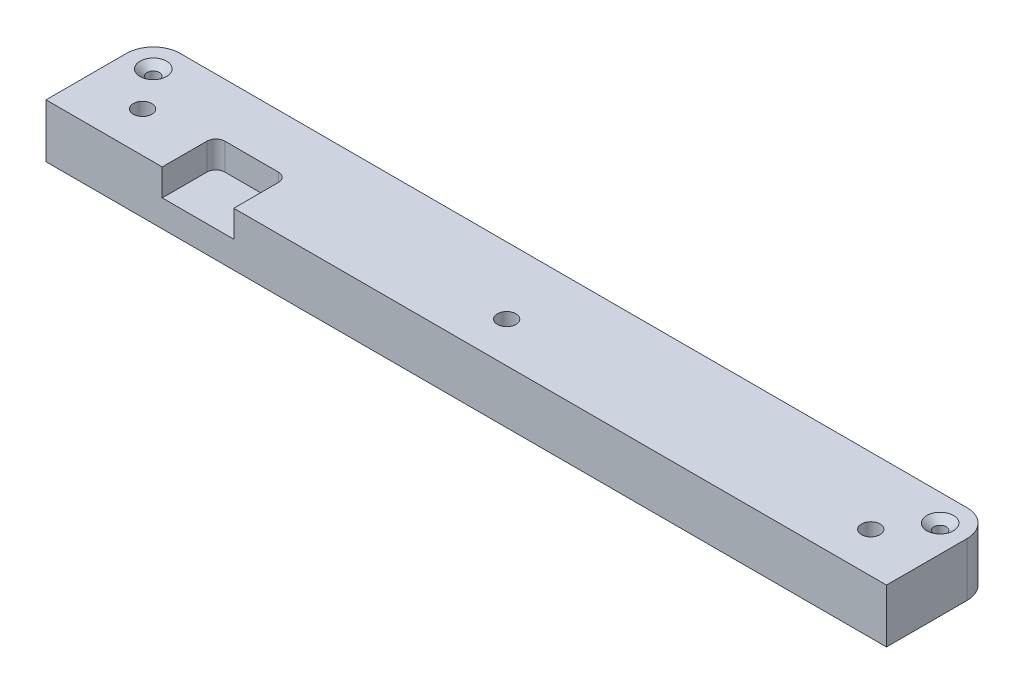
SolidWorks part; units mm, degrees
ref_plane "Front Plane" through (0, 0, 0) normal (0, 0, 1) x (1, 0, 0)
ref_plane "Top Plane" through (0, 0, 0) normal (0, 1, 0) x (1, 0, 0)
ref_plane "Right Plane" through (0, 0, 0) normal (1, 0, 0) x (0, 0, -1)
sketch "Sketch1" plane through (0, 0, 0) normal (0, 1, 0) x (1, 0, 0)
  line L1 (0, 0) -> (298.45, 0)
  line L2 (0, 0) -> (0, 38.1)
  line L3 (0, 38.1) -> (298.45, 38.1)
  line L4 (298.45, 0) -> (298.45, 38.1)
  dimension "D1" = 38.1
  dimension "D2" = 298.45
extrude "Boss-Extrude1" add sketch "Sketch1" along normal blind 19.05
fillet "Fillet1" radius 9.525 2 edges at (298.45, 9.525, -38.1) (0, 9.525, -38.1)
sketch "Sketch2" plane through (0, 19.05, 0) normal (0, 1, 0) x (1, 0, 0)
  line L0 (0, 14.351) -> (298.45, 14.351) construction
  line L1 (0, 28.575) -> (0, 0) construction
  line L2 (298.45, 0) -> (298.45, 28.575) construction
  line L3 (288.925, 38.1) -> (9.525, 38.1) construction
  circle A0 centre (19.939, 14.351) radius 3.302
  circle A1 centre (149.225, 14.351) radius 3.302
  circle A2 centre (278.511, 14.351) radius 3.302
  dimension "D2" = 6.604
  dimension "D1" = 23.749
  dimension "D3" = 19.939
  dimension "D4" = 19.939
extrude "Cut-Extrude1" cut sketch "Sketch2" against normal blind 14.2875
sketch "Sketch4" plane through (0, 0, 0) normal (0, -1, 0) x (1, 0, 0)
  circle A0 centre (19.939, -14.351) radius 1.4224
  circle A1 centre (149.225, -14.351) radius 1.4224
  circle A2 centre (278.511, -14.351) radius 1.4224
  dimension "D1" = 2.8448
extrude "Cut-Extrude2" cut sketch "Sketch4" against normal through all
sketch "Sketch5" plane through (0, 0, 0) normal (0, -1, 0) x (1, 0, 0)
  circle A0 centre (19.939, -14.351) radius 2.413
  circle A1 centre (149.225, -14.351) radius 2.413
  circle A2 centre (278.511, -14.351) radius 2.413
  dimension "D1" = 4.826
extrude "Cut-Extrude3" cut sketch "Sketch5" against normal blind 2.921
sketch "Sketch6" plane through (0, 19.05, 0) normal (0, 1, 0) x (1, 0, 0)
  line L0 (298.45, 28.575) -> (0, 28.575) construction
  line L1 (0, 28.575) -> (0, 0) construction
  line L2 (298.45, 0) -> (298.45, 28.575) construction
  circle A0 centre (9.525, 28.575) radius 2.1844
  circle A1 centre (288.925, 28.575) radius 2.1844
  dimension "D3" = 4.3688
  dimension "D1" = 9.525
  dimension "D2" = 9.525
extrude "Cut-Extrude4" cut sketch "Sketch6" against normal through all contours L0 A1 | A1 L0 | A0
chamfer "Chamfer1" distance 2.54 angle 41 2 edges at (288.925, 19.05, -26.3906) (9.525, 19.05, -26.3906)
sketch "Sketch7" plane through (0, 19.05, 0) normal (0, 1, 0) x (1, 0, 0)
  line L0 (288.925, 38.1) -> (9.525, 38.1) construction
  circle A0 centre (149.225, 28.575) radius 7.239
  dimension "D2" = 14.478
  dimension "D1" = 9.525
extrude "Cut-Extrude5" cut sketch "Sketch7" against normal through all from offset 5.08 offset against normal yes
sketch "Sketch8" plane through (0, 0, 0) normal (0, -1, 0) x (1, 0, 0)
  line L0 (0, 0) -> (298.45, 0) construction
  line L1 (41.275, 0) -> (66.675, 0)
  line L2 (41.275, 0) -> (41.275, -19.05)
  line L3 (41.275, -19.05) -> (66.675, -19.05)
  line L4 (66.675, 0) -> (66.675, -19.05)
  line L5 (0, -28.575) -> (0, 0) construction
  dimension "D1" = 41.275
  dimension "D2" = 25.4
  dimension "D3" = 19.05
extrude "Cut-Extrude6" cut sketch "Sketch8" against normal blind 9.525 from offset 9.525 offset against normal yes
fillet "Fillet2" radius 3.175 2 edges at (66.675, 14.2875, -19.05) (41.275, 14.2875, -19.05)
